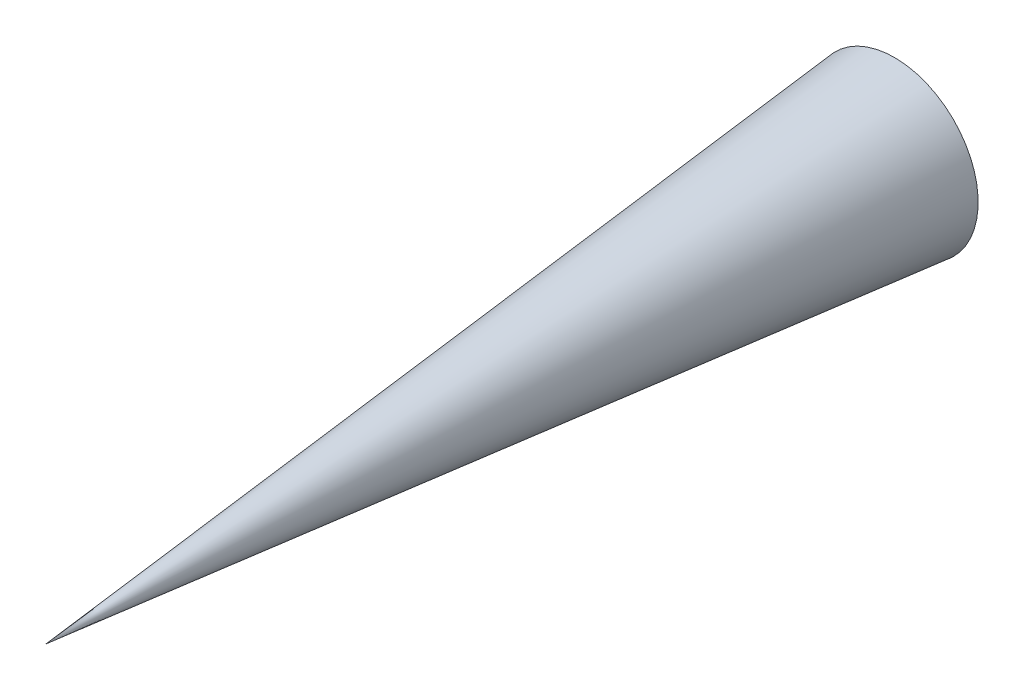
SolidWorks part; units mm, degrees
ref_plane "Front Plane" through (0, 0, 0) normal (0, 0, 1) x (1, 0, 0)
ref_plane "Top Plane" through (0, 0, 0) normal (0, 1, 0) x (1, 0, 0)
ref_plane "Right Plane" through (0, 0, 0) normal (1, 0, 0) x (0, 0, -1)
sketch "Sketch2" plane through (0, 0, 0) normal (1, 0, 0) x (0, 0, -1)
  line L0 (0, 0) -> (0, 50.8)
  line L1 (0, 0) -> (-515.4347, 0)
  spline S0 degree 4 poles (-567.3258, -5.1143) (-565.5546, -4.9397) (-560.5575, -4.4472) (-558.2723, -4.222) (-540.4273, -2.4632) (-518.9343, -0.3449) (-499.8533, 1.5357) (-452.2642, 6.2259) (-422.7963, 9.1302) (-381.3131, 13.2187) (-351.4434, 16.1626) (-319.014, 19.3587) (-291.8294, 22.038) (-263.9662, 24.7841) (-237.0381, 27.4381) (-209.9802, 30.1049) (-186.0209, 32.4662) (-165.0057, 34.5374) (-146.0416, 36.4065) (-129.6835, 38.0187) (-112.7946, 39.6832) (-97.4406, 41.1965) (-80.4277, 42.8732) (-64.2862, 44.4641) (-43.4991, 46.5128) (-28.9249, 47.9492) (-5.3977, 50.268) (4.9112, 51.284) (25.7025, 53.3332) (33.5358, 54.1052) (44.6735, 55.2029) (47.7054, 55.5017) (49.9605, 55.724) (51.1461, 55.8408) knots 0 0 0 0 0 0.010425 0.020851 0.041701 0.083403 0.146624 0.209844 0.26906 0.32799 0.382128 0.42325 0.467376 0.510644 0.558274 0.600254 0.640876 0.66655 0.694084 0.722691 0.747746 0.773897 0.796711 0.827511 0.8616 0.891685 0.917431 0.941514 0.973987 0.986994 0.993497 1 1 1 1 1 construction
  spline S1 degree 4 poles (-515.4347, 0) (-507.2881, 0.8029) (-491.1247, 2.3959) (-452.2642, 6.2259) (-422.7963, 9.1302) (-381.3131, 13.2187) (-351.4434, 16.1626) (-319.014, 19.3587) (-291.8294, 22.038) (-263.9662, 24.7841) (-237.0381, 27.4381) (-209.9802, 30.1049) (-186.0209, 32.4662) (-165.0057, 34.5374) (-146.0416, 36.4065) (-129.6835, 38.0187) (-112.7946, 39.6832) (-97.4406, 41.1965) (-80.4277, 42.8732) (-64.2862, 44.4641) (-43.4991, 46.5128) (-28.9249, 47.9492) (-10.3677, 49.7782) (-3.3176, 50.473) (0, 50.8) knots 0.083403 0.083403 0.083403 0.083403 0.083403 0.146624 0.209844 0.26906 0.32799 0.382128 0.42325 0.467376 0.510644 0.558274 0.600254 0.640876 0.66655 0.694084 0.722691 0.747746 0.773897 0.796711 0.827511 0.8616 0.891685 0.917431 0.917431 0.917431 0.917431 0.917431
  dimension "D1" = 50.8
revolve "Revolve1" add sketch "Sketch2" angle 360 about L1
equation "\"R\"= 2'base radius"
equation "\"L\"= 16.5'overall length"
equation "\"phi\"= atn ( \"R\" / \"L\" )"
